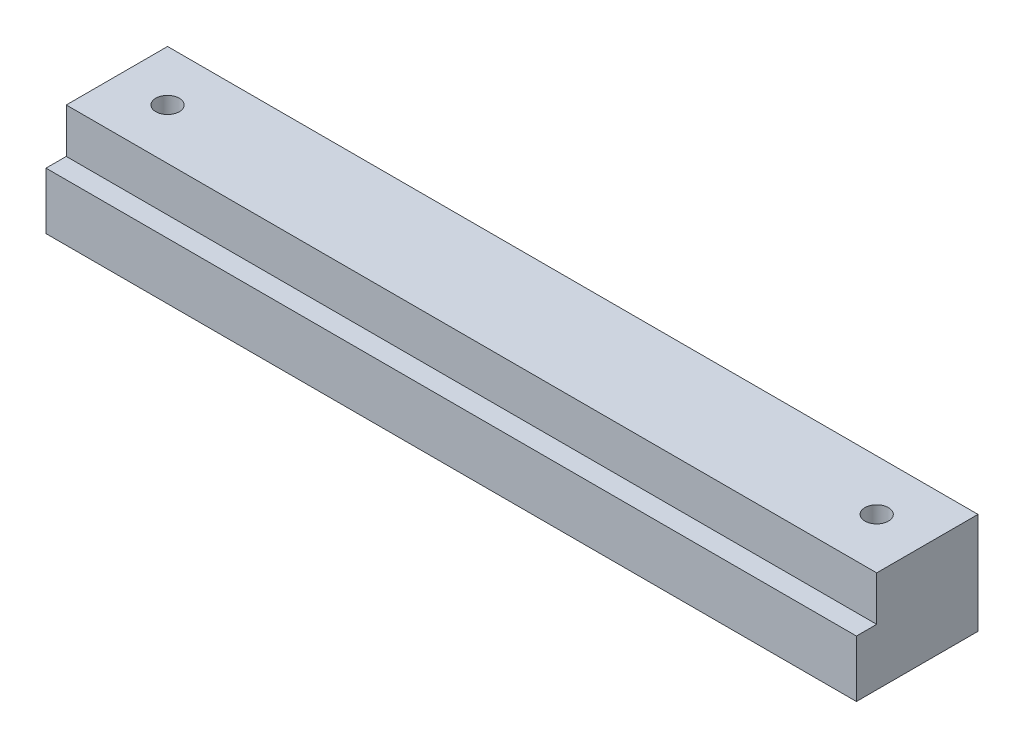
SolidWorks part; units mm, degrees
ref_plane "Front" through (0, 0, 0) normal (0, 0, 1) x (1, 0, 0)
ref_plane "Top" through (0, 0, 0) normal (0, 1, 0) x (1, 0, 0)
ref_plane "Right" through (0, 0, 0) normal (1, 0, 0) x (0, 0, -1)
sketch "Sketch1" plane through (0, 0, 0) normal (0, 1, 0) x (1, 0, 0)
  line L1 (0, 0) -> (101.6, 0)
  line L2 (0, 0) -> (0, 12.7)
  line L3 (0, 12.7) -> (101.6, 12.7)
  line L4 (101.6, 0) -> (101.6, 12.7)
  dimension "D1" = 12.7
  dimension "D2" = 101.6
extrude "Boss-Extrude1" add sketch "Sketch1" along normal blind 12.7
sketch "Sketch2" plane through (0, 12.7, 0) normal (0, 1, 0) x (1, 0, 0)
  line L0 (0, 6.35) -> (101.6, 6.35) construction
  line L1 (0, 12.7) -> (0, 0) construction
  line L2 (101.6, 0) -> (101.6, 12.7) construction
  point P6 (6.35, 6.35)
  point P7 (95.25, 6.35)
  dimension "D1" = 6.35
  dimension "D2" = 6.35
hole_wizard "#32 (0.116) Diameter Hole1" positions "Sketch3" profile "Sketch4" hole size "#32" standard "ANSI Inch" end condition through all
sketch "Sketch3" plane through (0, 12.7, 0) normal (0, 1, 0) x (1, 0, 0)
  point P0 (6.35, 6.35)
  point P3 (95.25, 6.35)
sketch "Sketch4" plane through (6.35, 12.7, -6.35) normal (1, 0, 0) x (0, 0, 1)
  line L0 (0, 0) -> (0, 12.7)
  line L1 (0, 12.7) -> (1.4732, 12.7)
  line L2 (1.4732, 12.7) -> (1.4732, 0)
  line L5 (1.4732, 0) -> (0, 0)
  line L11 (0, -6.35) -> (0, 107.95) construction
  dimension "Thru Hole Dia." = 2.9464
  dimension "Thru Hole Depth" = 12.7
sketch "Sketch5" plane through (0, 0, 0) normal (0, 0, 1) x (1, 0, 0)
  line L0 (101.6, 12.7) -> (101.6, 0) construction
  line L1 (0, 0) -> (101.6, 0)
  line L2 (0, 0) -> (0, 7.112)
  line L3 (0, 7.112) -> (101.6, 7.112)
  line L4 (101.6, 0) -> (101.6, 7.112)
  dimension "D1" = 7.112
extrude "Boss-Extrude2" add sketch "Sketch5" along normal blind 2.54
